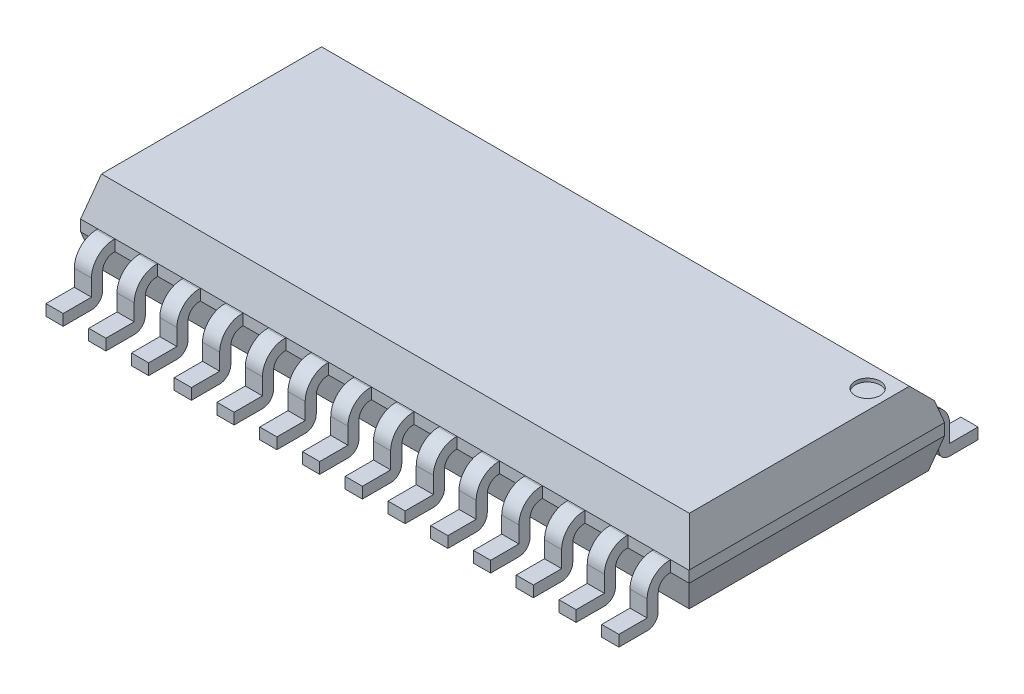
SolidWorks part; units mm, degrees
ref_plane "Front" through (0, 0, 0) normal (0, 0, 1) x (1, 0, 0)
ref_plane "Top" through (0, 0, 0) normal (0, 1, 0) x (1, 0, 0)
ref_plane "Right" through (0, 0, 0) normal (1, 0, 0) x (0, 0, -1)
sketch "Sketch1" plane through (0, 0, 0) normal (1, 0, 0) x (0, 0, -1)
  line L1 (0.2412, 0) -> (7.3488, 0)
  line L5 (0, 0.9) -> (0, 1.23)
  line L6 (0, 1.23) -> (0.3108, 2.39)
  line L7 (0, 0.9) -> (0.2412, 0)
  line L8 (7.59, 0.9) -> (7.59, 1.23)
  line L9 (7.59, 0.9) -> (7.3488, 0)
  line L10 (7.59, 1.23) -> (7.4363, 1.8037)
  line L11 (6.85, 2.39) -> (7.4363, 1.8037)
  line L12 (6.85, 2.39) -> (0.3108, 2.39)
  dimension "D1" = 2.39
  dimension "D2" = 7.59
  dimension "D3" = 15
  dimension "D4" = 15
  dimension "D5" = 45
extrude "Extrude1" add sketch "Sketch1" along normal blind 18.08
chamfer "Chamfer1" distance 1.15 angle 15 1 edges at (18.08, 2.39, -3.5804)
chamfer "Chamfer2" distance 0.9 angle 15 1 edges at (18.08, 0, -3.795)
chamfer "Chamfer3" distance 0.9 angle 15 1 edges at (0, 0, -3.795)
chamfer "Chamfer4" distance 1.15 angle 15 1 edges at (0, 2.39, -3.5804)
sketch "Sketch2" plane through (0, 0, -7.59) normal (0, 0, -1) x (-1, 0, 0)
  line L0 (-18.08, 1.23) -> (0, 1.23) construction
  line L1 (-17.53, 1.23) -> (-17.02, 1.23)
  line L2 (-17.53, 1.23) -> (-17.53, 0.9)
  line L3 (-17.53, 0.9) -> (-17.02, 0.9)
  line L4 (-17.02, 1.23) -> (-17.02, 0.9)
  line L5 (-18.08, 0.9) -> (0, 0.9) construction
  line L6 (-16.26, 1.23) -> (-15.75, 1.23)
  line L7 (-16.26, 1.23) -> (-16.26, 0.9)
  line L8 (-16.26, 0.9) -> (-15.75, 0.9)
  line L9 (-15.75, 1.23) -> (-15.75, 0.9)
  line L10 (-14.99, 1.23) -> (-14.48, 1.23)
  line L11 (-14.99, 1.23) -> (-14.99, 0.9)
  line L12 (-14.99, 0.9) -> (-14.48, 0.9)
  line L13 (-14.48, 1.23) -> (-14.48, 0.9)
  line L14 (-13.72, 1.23) -> (-13.21, 1.23)
  line L15 (-13.72, 1.23) -> (-13.72, 0.9)
  line L16 (-13.72, 0.9) -> (-13.21, 0.9)
  line L17 (-13.21, 1.23) -> (-13.21, 0.9)
  line L18 (-12.45, 1.23) -> (-11.94, 1.23)
  line L19 (-12.45, 1.23) -> (-12.45, 0.9)
  line L20 (-12.45, 0.9) -> (-11.94, 0.9)
  line L21 (-11.94, 1.23) -> (-11.94, 0.9)
  line L22 (-11.18, 1.23) -> (-10.67, 1.23)
  line L23 (-11.18, 1.23) -> (-11.18, 0.9)
  line L24 (-11.18, 0.9) -> (-10.67, 0.9)
  line L25 (-10.67, 1.23) -> (-10.67, 0.9)
  line L26 (-9.91, 1.23) -> (-9.4, 1.23)
  line L27 (-9.91, 1.23) -> (-9.91, 0.9)
  line L28 (-9.91, 0.9) -> (-9.4, 0.9)
  line L29 (-9.4, 1.23) -> (-9.4, 0.9)
  line L30 (-8.64, 1.23) -> (-8.13, 1.23)
  line L31 (-8.64, 1.23) -> (-8.64, 0.9)
  line L32 (-8.64, 0.9) -> (-8.13, 0.9)
  line L33 (-8.13, 1.23) -> (-8.13, 0.9)
  line L34 (-7.37, 1.23) -> (-6.86, 1.23)
  line L35 (-7.37, 1.23) -> (-7.37, 0.9)
  line L36 (-7.37, 0.9) -> (-6.86, 0.9)
  line L37 (-6.86, 1.23) -> (-6.86, 0.9)
  line L38 (-6.1, 1.23) -> (-5.59, 1.23)
  line L39 (-6.1, 1.23) -> (-6.1, 0.9)
  line L40 (-6.1, 0.9) -> (-5.59, 0.9)
  line L41 (-5.59, 1.23) -> (-5.59, 0.9)
  line L42 (-4.83, 1.23) -> (-4.32, 1.23)
  line L43 (-4.83, 1.23) -> (-4.83, 0.9)
  line L44 (-4.83, 0.9) -> (-4.32, 0.9)
  line L45 (-4.32, 1.23) -> (-4.32, 0.9)
  line L46 (-3.56, 1.23) -> (-3.05, 1.23)
  line L47 (-3.56, 1.23) -> (-3.56, 0.9)
  line L48 (-3.56, 0.9) -> (-3.05, 0.9)
  line L49 (-3.05, 1.23) -> (-3.05, 0.9)
  line L50 (-2.29, 1.23) -> (-1.78, 1.23)
  line L51 (-2.29, 1.23) -> (-2.29, 0.9)
  line L52 (-2.29, 0.9) -> (-1.78, 0.9)
  line L53 (-1.78, 1.23) -> (-1.78, 0.9)
  line L54 (-1.02, 1.23) -> (-0.51, 1.23)
  line L55 (-1.02, 1.23) -> (-1.02, 0.9)
  line L56 (-1.02, 0.9) -> (-0.51, 0.9)
  line L57 (-0.51, 1.23) -> (-0.51, 0.9)
  line L59 (-18.08, 0.9) -> (-18.08, 1.23) construction
  dimension "D1" = 0.51
  dimension "D2" = 0.55
sketch "Sketch3" plane through (0, 0, 0) normal (-1, 0, 0) x (0, 0, 1)
  line L0 (-7.59, 0.9) -> (-7.63, 0.9)
  line L1 (-7.96, 0.57) -> (-7.96, 0.08)
  line L2 (-9.13, -0.25) -> (-8.29, -0.25)
  line L3 (-0.2412, 0) -> (-7.3488, 0) construction
  line L4 (-7.59, 1.23) -> (-7.59, 0.9) construction
  arc A0 (-7.96, 0.57) -> (-7.63, 0.9) centre (-7.63, 0.57) cw
  arc A1 (-7.96, 0.08) -> (-8.29, -0.25) centre (-8.29, 0.08) cw
  dimension "D3" = 0.33
  dimension "D4" = 0.33
  dimension "D1" = 0.25
  dimension "D2" = 1.54
  dimension "D5" = 0.84
sweep "Sweep1" add profiles "Sketch2" path "Sketch3"
ref_plane "Plane1" through (0, 0, -3.795) normal (0, 0, 1) x (1, 0, 0)
mirror "Mirror1" about plane through (0, 0, -3.795) normal (0, 0, 1) of "Sweep1"
sketch "Sketch4" plane through (0, 2.39, 0) normal (0, 1, 0) x (1, 0, 0)
  circle A0 centre (17.2066, 6.1751) radius 0.3712
extrude "Cut-Extrude1" cut sketch "Sketch4" against normal blind 0.1
